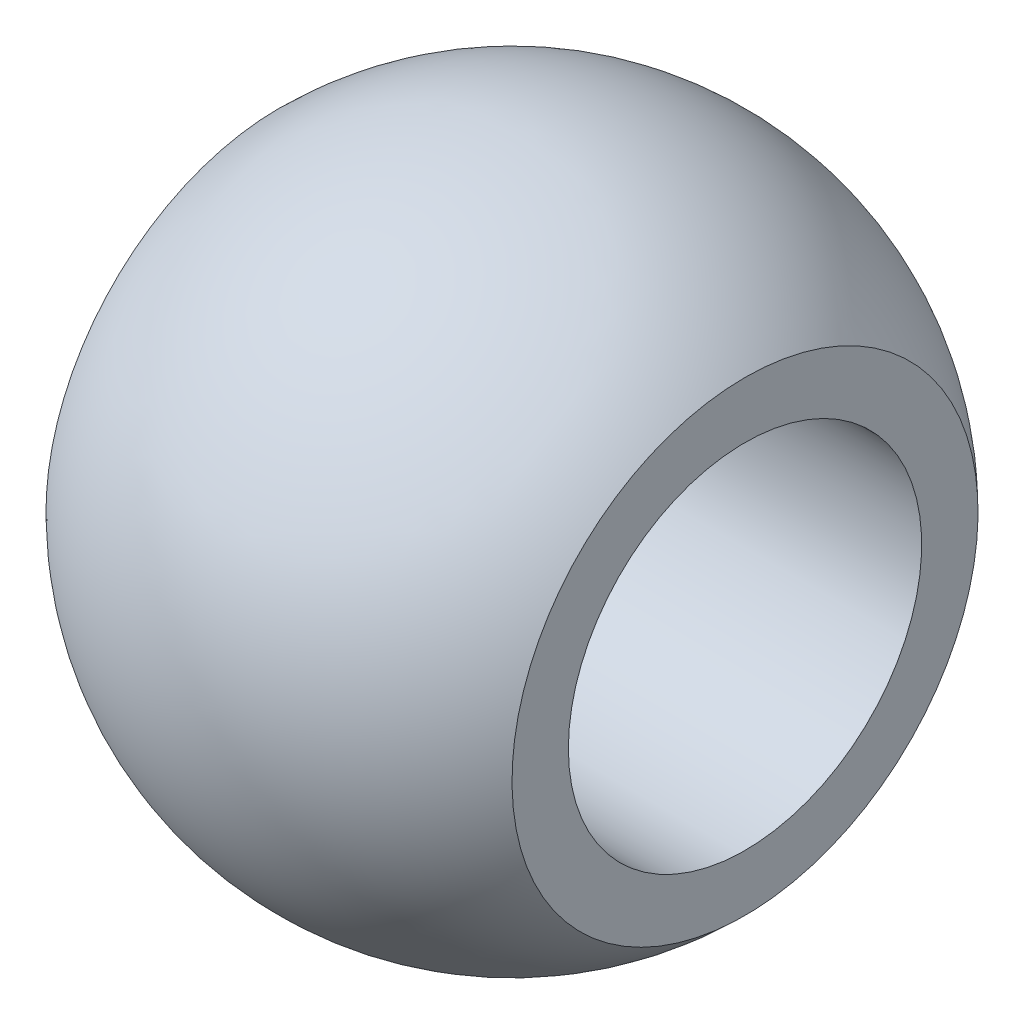
SolidWorks part; units mm, degrees
ref_plane "Front Plane" through (0, 0, 0) normal (0, 0, 1) x (1, 0, 0)
ref_plane "Top Plane" through (0, 0, 0) normal (0, 1, 0) x (1, 0, 0)
ref_plane "Right Plane" through (0, 0, 0) normal (1, 0, 0) x (0, 0, -1)
sketch "Sketch1" plane through (0, 0, 0) normal (0, 0, 1) x (1, 0, 0)
  line L0 (-15.2153, 0) -> (26.6969, 0) construction
  line L1 (-4.5, -4.5) -> (4.5, -4.5)
  line L2 (-4.5, -4.5) -> (-4.5, -3.4115)
  line L3 (-4.5, 4.5) -> (4.5, 4.5)
  line L4 (4.5, -4.5) -> (4.5, -3.4115)
  line L5 (-4.5, -4.5) -> (3.4115, 3.4115) construction
  line L6 (-4.5, 4.5) -> (4.5, -4.5) construction
  line L7 (-4.5, -3.4115) -> (4.5, -3.4115)
  line L8 (-4.5, 4.5) -> (-5.539, 4.5)
  line L9 (-4.5, 3.4115) -> (4.5, 3.4115)
  line L10 (4.5, 3.4115) -> (4.5, 4.5)
  line L11 (-4.5, -3.4115) -> (4.5, 3.4115) construction
  line L12 (-4.5, 3.4115) -> (4.5, -3.4115) construction
  line L13 (4.5, 4.5) -> (6.0073, 4.5)
  line L19 (5.9795, -3.4115) -> (4.5, -3.4115)
  line L20 (-4.5, 3.4115) -> (-4.5, 4.5)
  line L26 (-5.7025, -3.4115) -> (-4.5, -3.4115)
  arc A0 (-4.5, -4.5) -> (4.5, -4.5) centre (0, 0) ccw
  arc A1 (4.5, 4.5) -> (-4.5, 4.5) centre (0, 0) ccw
  dimension "D1" = 4.5
  dimension "D3" = 3.4115
  dimension "D2" = 9
revolve "Revolve1" add sketch "Sketch1" angle 360 about L0
